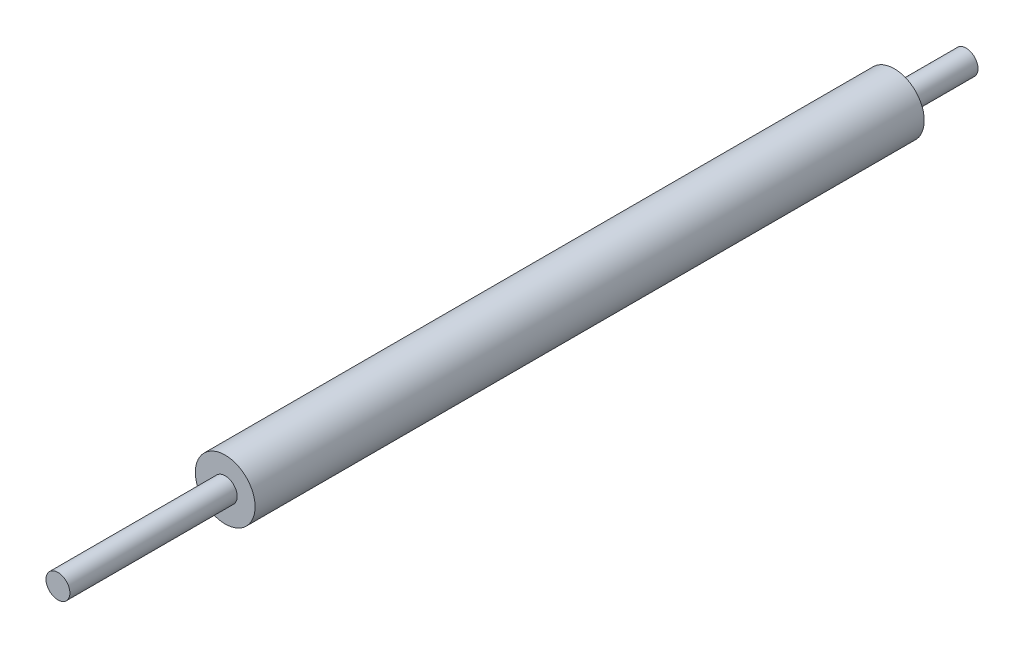
SolidWorks part; units mm, degrees
ref_plane "Front Plane" through (0, 0, 0) normal (0, 0, 1) x (1, 0, 0)
ref_plane "Top Plane" through (0, 0, 0) normal (0, 1, 0) x (1, 0, 0)
ref_plane "Right Plane" through (0, 0, 0) normal (1, 0, 0) x (0, 0, -1)
sketch "Sketch1" plane through (0, 0, 0) normal (0, 0, 1) x (1, 0, 0)
  circle A0 centre (0, 0) radius 12.5
  dimension "D1" = 25
extrude "Boss-Extrude1" add sketch "Sketch1" along normal blind 280
sketch "Sketch2" plane through (0, 0, 280) normal (0, 0, 1) x (1, 0, 0)
  circle A0 centre (0, 0) radius 5
  dimension "D1" = 10
extrude "Boss-Extrude2" add sketch "Sketch2" along normal blind 70
sketch "Sketch3" plane through (0, 0, 0) normal (0, 0, -1) x (-1, 0, 0)
  circle A0 centre (0, 0) radius 5
  dimension "D1" = 10
extrude "Boss-Extrude3" add sketch "Sketch3" along normal blind 30
